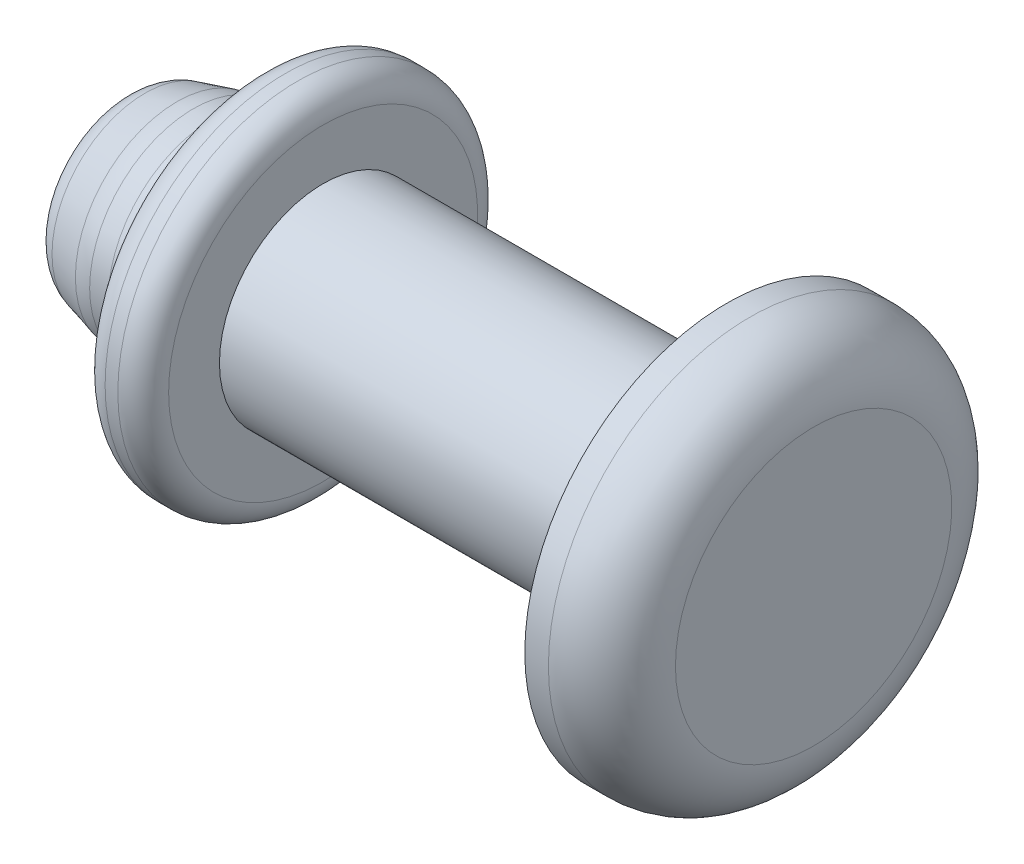
SolidWorks part; units mm, degrees
material "A286 Iron Base Superalloy"
ref_plane "Front Plane" through (0, 0, 0) normal (0, 0, 1) x (1, 0, 0)
ref_plane "Top Plane" through (0, 0, 0) normal (0, 1, 0) x (1, 0, 0)
ref_plane "Right Plane" through (0, 0, 0) normal (1, 0, 0) x (0, 0, -1)
sketch "Sketch2" plane through (0, 0, 0) normal (0, 0, 1) x (1, 0, 0)
  line L0 (-42.3, 0) -> (42.3, 0) construction
  line L1 (0, 0) -> (0, 2.175)
  line L2 (-1, 3.175) -> (-1.3716, 3.175)
  line L3 (-1.3716, 3.175) -> (-1.3716, 1.632)
  line L4 (-1.3716, 1.632) -> (-7.7216, 1.6319)
  line L5 (-7.7216, 1.6319) -> (-7.7216, 2.4319)
  line L10 (-7.7216, 2.8319) -> (-7.7216, 0) construction
  line L11 (-1.3716, 3.175) -> (-1.3716, 0) construction
  line L12 (0, 0) -> (-10.8966, 0)
  line L15 (-8.1216, 2.8319) -> (-8.3216, 2.8319)
  line L16 (-8.7216, 2.4319) -> (-8.7216, 2.382)
  line L18 (-9.4716, 1.6319) -> (-9.7649, 1.6319)
  line L19 (-10.8966, 0.9803) -> (-10.8966, 0)
  line L20 (-10.0238, 1.5979) -> (-10.526, 1.4633)
  arc A0 (0, 2.175) -> (-1, 3.175) centre (-1, 2.175) ccw
  arc A6 (-8.7216, 2.4319) -> (-8.3216, 2.8319) centre (-8.3216, 2.4319) cw
  arc A7 (-7.7216, 2.4319) -> (-8.1216, 2.8319) centre (-8.1216, 2.4319) ccw
  arc A8 (-9.4716, 1.6319) -> (-8.7216, 2.382) centre (-9.4716, 2.3819) ccw
  arc A9 (-9.7649, 1.6319) -> (-10.0238, 1.5979) centre (-9.7649, 0.6319) ccw
  arc A10 (-10.8966, 0.9803) -> (-10.526, 1.4633) centre (-10.3966, 0.9803) cw
  point P4 (0, 0)
  point P14 (-10.8966, 1.6319)
  point P18 (0, 3.175)
  point P30 (-10.8966, 1.6319)
  point P33 (-9.8966, 1.6319)
  dimension "D9" = 1
  dimension "D13" = 0.4
  dimension "D16" = 0.75
  dimension "D14" = 1
  dimension "D15" = 0.5
  dimension "D2" = 3.175
  dimension "D3" = 1.632
  dimension "D4" = 6.35
  dimension "D5" = 1.3716
  dimension "D8" = 1.632
  dimension "D7" = 1.2
  dimension "D10" = 1
  dimension "D6" = 3.175
  dimension "D11" = 1
  dimension "D12" = 15
revolve "Revolve1" add sketch "Sketch2" angle 360 about L0
equation "\"Grip Length\"= 0.250in"
equation "\"Rivet Head Height\"= .054in"
equation "\"Rivet Head Radius\"= .250in / 2"
equation "\"Radius Shaft\"= 0.1285in'CHERRY CR1919-04"
equation "\"D2@Sketch2\"=\"Rivet Head Radius\""
equation "\"D3@Sketch2\"=\"Rivet Shank\""
equation "\"D4@Sketch2\"=\"Grip Length\""
equation "\"D5@Sketch2\"=\"Rivet Head Height\""
equation "\"Rivet Shank\"= 0.1285in / 2'CHERRY CR1919-04"
equation "\"D8@Sketch2\"=\"Rivet Shank\""
equation "\"D6@Sketch2\"=\"Grip Length\"/2"
